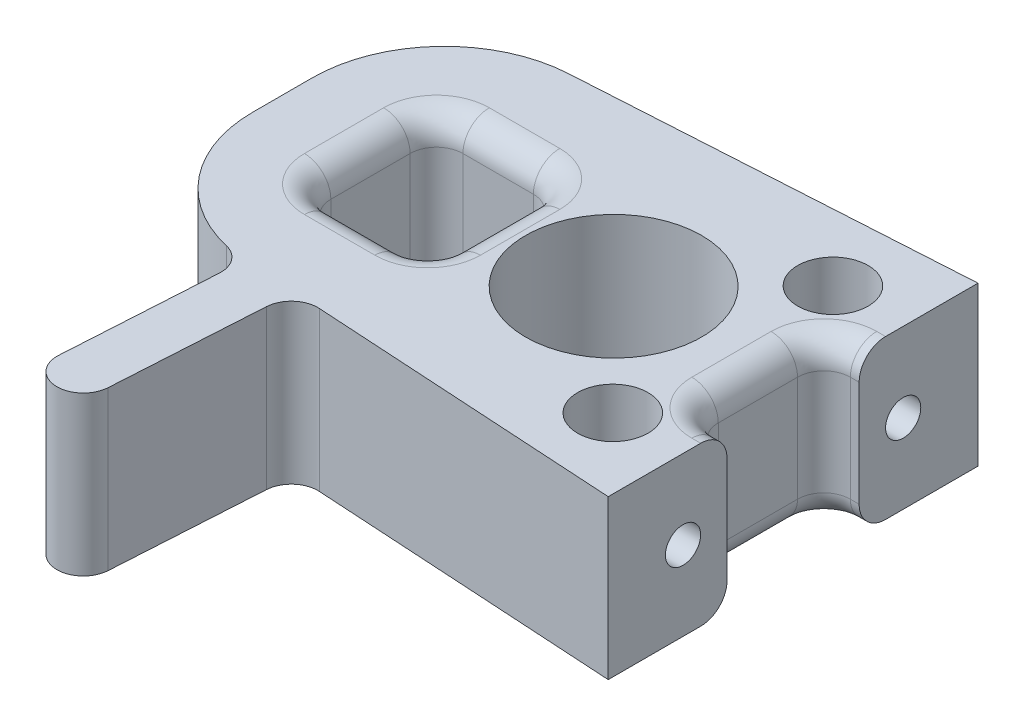
SolidWorks part; units mm, degrees
material "PE High Density"
ref_plane "Front Plane" through (0, 0, 0) normal (0, 0, 1) x (1, 0, 0)
ref_plane "Top Plane" through (0, 0, 0) normal (0, 1, 0) x (1, 0, 0)
ref_plane "Right Plane" through (0, 0, 0) normal (1, 0, 0) x (0, 0, -1)
sketch "Sketch1" plane through (0, 0, 0) normal (0, 1, 0) x (1, 0, 0)
  line L0 (-17, 17.5) -> (41, 21)
  line L1 (41, 21) -> (41, 7.5)
  line L2 (41, 7.5) -> (37, 7.5)
  line L3 (37, 7.5) -> (37, -7.5)
  line L4 (37, -7.5) -> (41, -7.5)
  line L5 (41, -7.5) -> (41, -21)
  line L6 (41, -21) -> (-17, -17.5)
  line L7 (-17, -17.5) -> (-17, 17.5)
  line L8 (-7, 7.5) -> (7, 7.5)
  line L9 (-7, 7.5) -> (-7, -7.5)
  line L10 (7, 7.5) -> (7, -7.5)
  line L11 (-7, -7.5) -> (7, -7.5)
  line L12 (-7, 7.5) -> (7, -7.5) construction
  line L13 (7, 7.5) -> (-7, -7.5) construction
  line L14 (-17, 7.5) -> (-7, 7.5) construction
  line L15 (7, 0) -> (37, 0) construction
  point P9 (0, 0)
  dimension "D6" = 58
  dimension "D1" = 15
  dimension "D2" = 35
  dimension "D3" = 4
  dimension "D4" = 30
  dimension "D5" = 14
  dimension "D7" = 42
extrude "Boss-Extrude1" add sketch "Sketch1" along normal blind 18
fillet "Fillet1" radius 15 2 edges at (-17, 9, -17.5) (-17, 9, 17.5)
fillet "Fillet2" radius 3 20 edges at (0, 18, -7.5) (39, 0, -7.5) (37, 0, 0) (39, 0, 7.5) (39, 18, -7.5) (37, 18, 0) (39, 18, 7.5) (-7, 0, 0) (0, 0, 7.5) (0, 0, -7.5) (7, 0, 0) (-7, 18, 0) (0, 18, 7.5) (7, 18, 0) (7, 9, -7.5) (37, 9, 7.5) (37, 9, -7.5) (7, 9, 7.5) (-7, 9, 7.5) (-7, 9, -7.5)
sketch "Sketch2" plane through (41, 0, 0) normal (1, 0, 0) x (0, 0, -1)
  line L0 (-15.75, 18) -> (-9.25, 0) construction
  line L1 (-21, 18) -> (-10.5, 18) construction
  line L2 (-21, 0) -> (-10.5, 0) construction
  line L3 (-12.5, 9) -> (12.5, 9) construction
  line L4 (10.5, 18) -> (21, 18) construction
  line L5 (13.2226, 18) -> (11.7774, 0) construction
  line L6 (10.5, 0) -> (21, 0) construction
  line L8 (0, 0) -> (0, 9) construction
  circle A0 centre (-12.5, 9) radius 2
  circle A1 centre (12.5, 9) radius 2
  dimension "D2" = 4
  dimension "D1" = 25
extrude "Cut-Extrude1" cut sketch "Sketch2" against normal blind 50
sketch "Sketch3" plane through (0, 18, 0) normal (0, 1, 0) x (1, 0, 0)
  line L0 (33.0243, -12.5) -> (41, -12.5) construction
  line L1 (41, -21) -> (41, -10.5) construction
  line L2 (41, 10.5) -> (41, 14.5) construction
  line L3 (33.0243, 12.5) -> (41, 12.5) construction
  line L4 (41, 10.5) -> (41, 21) construction
  line L5 (41, -14.5) -> (41, -10.5) construction
  line L6 (7, -4.5) -> (7, 4.5) construction
  line L7 (0, 0) -> (20.6142, 0) construction
  circle A0 centre (33.0243, -12.5) radius 4
  circle A1 centre (33.0243, 12.5) radius 4
  circle A2 centre (33.0243, 12.5) radius 7.6142 construction
  arc A3 (40, 7.5) -> (37, 4.5) centre (40, 4.5) ccw construction
  circle A5 centre (20.6142, 0) radius 10
  circle A6 centre (20.6142, 0) radius 13.6142 construction
  dimension "D1" = 8
  dimension "D2" = 20
extrude "Cut-Extrude2" cut sketch "Sketch3" against normal blind 15
sketch "Sketch4" plane through (0, 3, 0) normal (0, 1, 0) x (1, 0, 0)
  circle A1 centre (20.6142, 0) radius 10
  circle A2 centre (20.6142, 0) radius 10
  dimension "D1" = 0
extrude "Cut-Extrude3" cut sketch "Sketch4" against normal blind 17
sketch "Sketch5" plane through (0, 18, 0) normal (0, 1, 0) x (1, 0, 0)
  line L0 (-1.1137, -38.495) -> (0.091, -18.5314) construction
  line L1 (-2.9035, -18.3506) -> (41, -21) construction
  line L2 (-4.1082, -38.3143) -> (-2.9035, -18.3506)
  line L3 (1.8809, -38.6757) -> (3.0856, -18.7121)
  arc A0 (-4.1082, -38.3143) -> (1.8809, -38.6757) centre (-1.1137, -38.495) ccw
  arc A1 (3.0856, -18.7121) -> (-2.9035, -18.3506) centre (0.091, -18.5314) ccw
  point P4 (-0.5113, -28.5132)
  point P9 (-1.2944, -41.4896)
  dimension "D1" = 3
  dimension "D2" = 23
extrude "Boss-Extrude2" add sketch "Sketch5" against normal blind 18
fillet "Fillet3" radius 3 2 edges at (3.0856, 9, 18.7121) (-2.9035, 9, 18.3506)
